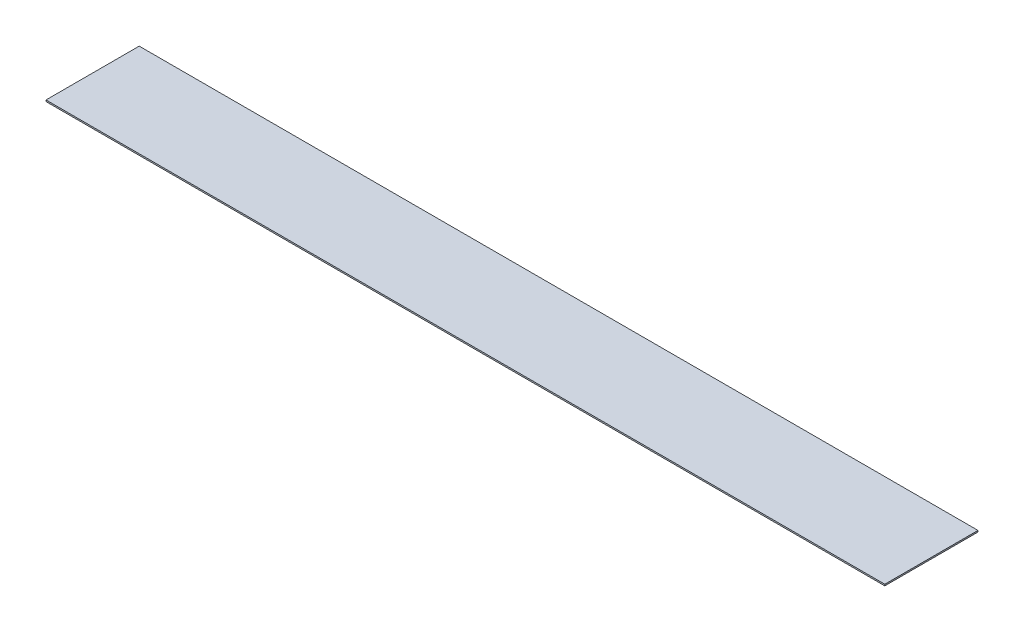
SolidWorks part; units mm, degrees
material "Nylon 101"
ref_plane "Front Plane" through (0, 0, 0) normal (0, 0, 1) x (1, 0, 0)
ref_plane "Top Plane" through (0, 0, 0) normal (0, 1, 0) x (1, 0, 0)
ref_plane "Right Plane" through (0, 0, 0) normal (1, 0, 0) x (0, 0, -1)
sketch "Sketch1" plane through (0, 0, 0) normal (0, 1, 0) x (1, 0, 0)
  line L1 (0, 0) -> (914.4, 0)
  line L2 (0, 0) -> (0, 101.6)
  line L3 (0, 101.6) -> (914.4, 101.6)
  line L4 (914.4, 0) -> (914.4, 101.6)
  dimension "D1" = 101.6
  dimension "D2" = 914.4
extrude "Boss-Extrude1" add sketch "Sketch1" along normal blind 1.5875
